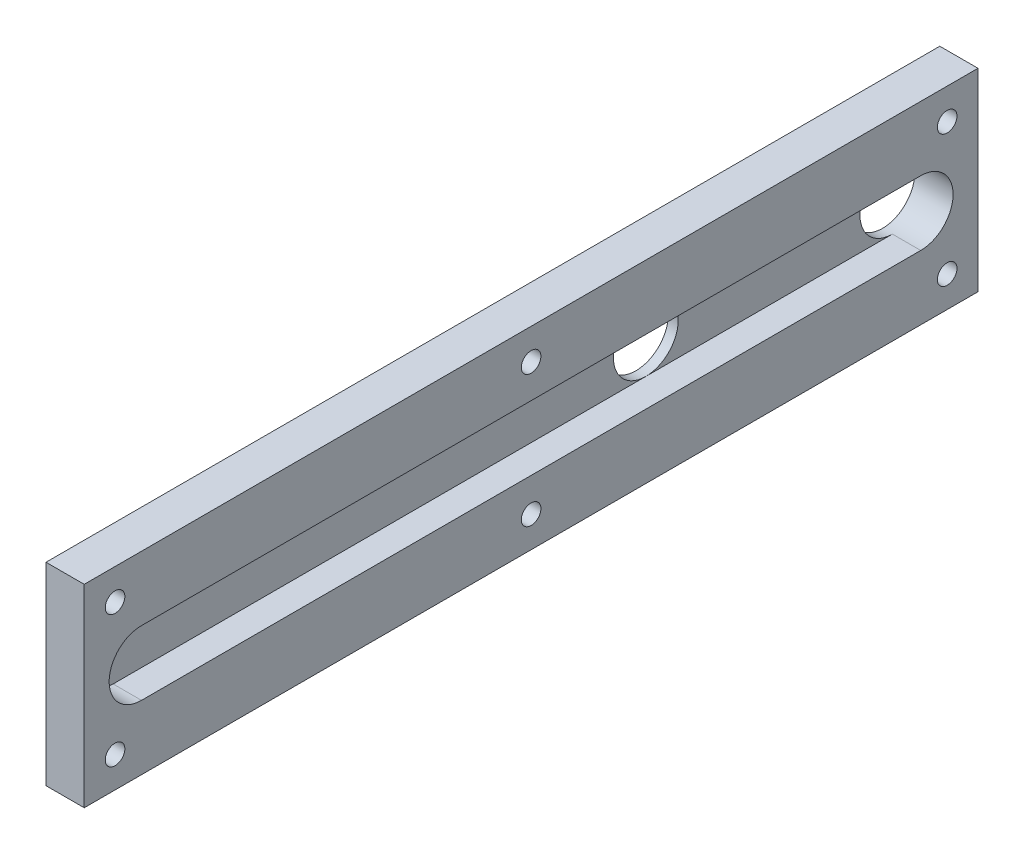
SolidWorks part; units mm, degrees
material "Delrin 2700 NC010, Low Viscosity Acetal Copolymer (SS)"
ref_plane "Front" through (0, 0, 0) normal (0, 0, 1) x (1, 0, 0)
ref_plane "Top" through (0, 0, 0) normal (0, 1, 0) x (1, 0, 0)
ref_plane "Right" through (0, 0, 0) normal (1, 0, 0) x (0, 0, -1)
sketch "Sketch1" plane through (0, 0, 0) normal (1, 0, 0) x (0, 0, -1)
  line L0 (-80.2752, 0) -> (80.2752, 0) construction
  line L1 (92.075, -19.939) -> (-92.075, -19.939)
  line L2 (92.075, -19.939) -> (92.075, 19.939)
  line L3 (92.075, 19.939) -> (-92.075, 19.939)
  line L4 (-92.075, -19.939) -> (-92.075, 19.939)
  line L5 (92.075, -19.939) -> (-92.075, 19.939) construction
  line L6 (92.075, 19.939) -> (-92.075, -19.939) construction
  line L7 (-80.2752, 6.6675) -> (80.2752, 6.6675)
  line L8 (-80.2752, -6.6675) -> (80.2752, -6.6675)
  arc A0 (-80.2752, 6.6675) -> (-80.2752, -6.6675) centre (-80.2752, 0) ccw
  arc A1 (80.2752, -6.6675) -> (80.2752, 6.6675) centre (80.2752, 0) ccw
  point P0 (0, 0)
  point P8 (0, 0)
  dimension "D4" = 13.335
  dimension "D1" = 160.5505
  dimension "D2" = 184.15
  dimension "D3" = 39.878
extrude "Boss-Extrude1" add sketch "Sketch1" along normal blind 7.874
hole_wizard "#10-32 Tapped Hole1" positions "Sketch3" profile "Sketch4" tap size "#10-32" standard "ANSI Inch" end condition through all
sketch "Sketch3" plane through (7.874, 0, 0) normal (1, 0, 0) x (0, 0, -1)
  line L0 (-85.725, 13.589) -> (0, 13.589) construction
  line L1 (0, 13.589) -> (85.725, 13.589) construction
  line L3 (-85.725, 19.939) -> (-85.725, 13.589) construction
  line L4 (92.075, 19.939) -> (-92.075, 19.939) construction
  line L5 (-85.725, 13.589) -> (-85.725, -13.589) construction
  line L6 (-85.725, -13.589) -> (-85.725, -19.939) construction
  line L7 (-92.075, -19.939) -> (92.075, -19.939) construction
  line L8 (-92.075, 19.939) -> (-92.075, -19.939) construction
  point P0 (-85.725, 13.589)
  point P2 (-85.725, -13.589)
  point P4 (0, -13.589)
  point P6 (85.725, -13.589)
  point P8 (85.725, 13.589)
  point P10 (0, 13.589)
  dimension "D1" = 6.35
  dimension "D2" = 6.35
sketch "Sketch4" plane through (7.874, 13.589, 85.725) normal (0, 1, 0) x (0, 0, -1)
  line L0 (0, 0) -> (0, 7.874)
  line L1 (0, 7.874) -> (2.0193, 7.874)
  line L2 (2.0193, 7.874) -> (2.0193, 0)
  line L5 (2.0193, 0) -> (0, 0)
  line L11 (0, -6.35) -> (0, 107.95) construction
  dimension "Thru Tap Drill Dia." = 4.0386
  dimension "Thru Tap Drill Depth" = 7.874
cosmetic thread "Hole Thread1" parameters "D2"=4.826
cosmetic thread "Hole Thread2" parameters "D2"=4.826
cosmetic thread "Hole Thread3" parameters "D2"=4.826
cosmetic thread "Hole Thread4" parameters "D2"=4.826
cosmetic thread "Hole Thread5" parameters "D2"=4.826
cosmetic thread "Hole Thread6" parameters "D2"=4.826
sketch "Sketch5" plane through (0, 0, 0) normal (-1, 0, 0) x (0, 0, 1)
  line L6 (-80.2752, -6.6675) -> (80.2752, -6.6675)
  line L7 (80.2752, 6.6675) -> (-80.2752, 6.6675)
  line L8 (-80.2752, -6.6675) -> (80.2752, -6.6675)
  line L9 (80.2752, 6.6675) -> (-80.2752, 6.6675)
  arc A1 (-80.2752, -6.6675) -> (-80.2752, 6.6675) centre (-80.2752, 0) ccw
  arc A7 (80.2752, -6.6675) -> (80.2752, 6.6675) centre (80.2752, 0) ccw
  arc A8 (-80.2752, 6.6675) -> (-80.2752, -6.6675) centre (-80.2752, 0) ccw
  arc A9 (80.2752, -6.6675) -> (80.2752, 6.6675) centre (80.2752, 0) ccw
  arc A11 (-80.2752, 6.6675) -> (-80.2752, -6.6675) centre (-80.2752, 0) ccw construction
  circle A12 centre (-29.4752, 0) radius 6.6675
  arc M15 (80.2752, 6.6675) -> (80.2752, -6.6675) centre (80.2752, 0) cw
  line M16 (80.2752, -6.6675) -> (-80.2752, -6.6675)
  line M18 (-80.2752, 6.6675) -> (80.2752, 6.6675)
  dimension "D2" = 50.8
  dimension "D1" = 0
extrude "Boss-Extrude2" add sketch "Sketch5" against normal blind 2.032 contours A12 A1 L8 M18 | A12 L9 M16 M15
